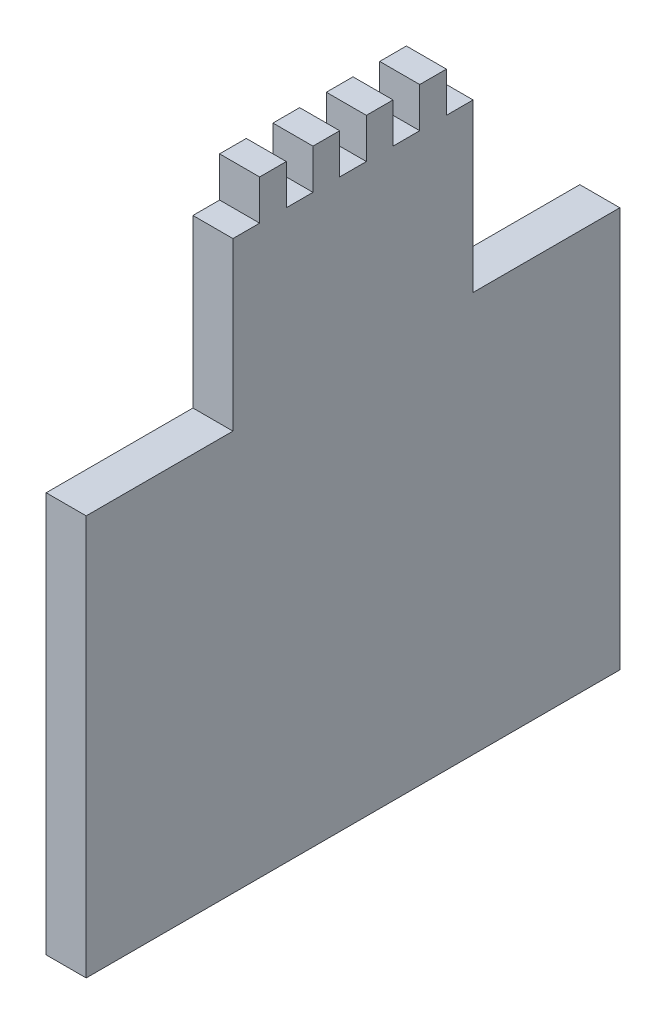
SolidWorks part; units mm, degrees
ref_plane "Front Plane" through (0, 0, 0) normal (0, 0, 1) x (1, 0, 0)
ref_plane "Top Plane" through (0, 0, 0) normal (0, 1, 0) x (1, 0, 0)
ref_plane "Right Plane" through (0, 0, 0) normal (1, 0, 0) x (0, 0, -1)
sketch "Sketch1" plane through (0, 0, 0) normal (1, 0, 0) x (0, 0, -1)
  line L0 (-9, 12.5) -> (-9, 0)
  line L1 (-9, 0) -> (-20, 0)
  line L2 (-20, 0) -> (-20, -30)
  line L3 (-20, -30) -> (20, -30)
  line L4 (20, -30) -> (20, 0)
  line L5 (20, 0) -> (9, 0)
  line L6 (9, 0) -> (9, 12.5)
  line L8 (-7, 15.5) -> (-7, 12.5)
  line L10 (-5, 12.5) -> (-5, 15.5)
  line L12 (-3, 15.5) -> (-3, 12.5)
  line L14 (-1, 12.5) -> (-1, 15.5)
  line L16 (1, 15.5) -> (1, 12.5)
  line L18 (3, 12.5) -> (3, 15.5)
  line L20 (5, 15.5) -> (5, 12.5)
  line L22 (7, 12.5) -> (7, 15.5)
  line L24 (-7, 15.5) -> (-5, 15.5)
  line L25 (-3, 15.5) -> (-1, 15.5)
  line L26 (1, 15.5) -> (3, 15.5)
  line L28 (5, 15.5) -> (7, 15.5)
  line L30 (-7, 12.5) -> (-9, 12.5)
  line L31 (-5, 12.5) -> (-3, 12.5)
  line L32 (-1, 12.5) -> (1, 12.5)
  line L33 (3, 12.5) -> (5, 12.5)
  line L34 (7, 12.5) -> (9, 12.5)
  point P6 (0, -30)
  point P8 (0, 12.5)
  dimension "D1" = 30
  dimension "D2" = 40
  dimension "D3" = 3
  dimension "D4" = 18
  dimension "D5" = 15.5
extrude "Boss-Extrude1" add sketch "Sketch1" along normal blind 3
